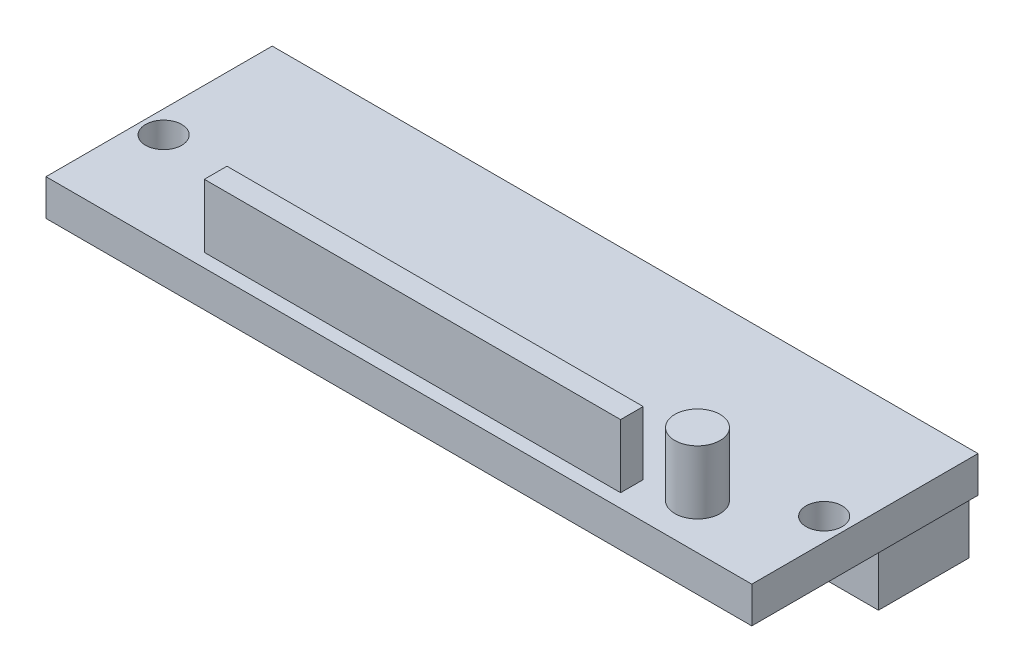
SolidWorks part; units mm, degrees
ref_plane "Front Plane" through (0, 0, 0) normal (0, 0, 1) x (1, 0, 0)
ref_plane "Top Plane" through (0, 0, 0) normal (0, 1, 0) x (1, 0, 0)
ref_plane "Right Plane" through (0, 0, 0) normal (1, 0, 0) x (0, 0, -1)
sketch "Sketch1" plane through (0, 0, 0) normal (0, 1, 0) x (1, 0, 0)
  line L1 (-39, -12.5) -> (39, -12.5)
  line L2 (-39, -12.5) -> (-39, 12.5)
  line L3 (-39, 12.5) -> (39, 12.5)
  line L4 (39, -12.5) -> (39, 12.5)
  line L5 (-39, -12.5) -> (39, 12.5) construction
  line L6 (-39, 12.5) -> (39, -12.5) construction
  point P0 (0, 0)
  dimension "D1" = 78
  dimension "D2" = 25
extrude "Boss-Extrude1" add sketch "Sketch1" along normal blind 4
sketch "Sketch2" plane through (0, 4, 0) normal (0, 1, 0) x (1, 0, 0)
  line L0 (-39, -12.5) -> (39, -12.5) construction
  line L1 (-23, -11) -> (23, -11)
  line L2 (-23, -11) -> (-23, -8.5)
  line L3 (-23, -8.5) -> (23, -8.5)
  line L4 (23, -11) -> (23, -8.5)
  line L5 (-23, -11) -> (23, -8.5) construction
  line L6 (-23, -8.5) -> (23, -11) construction
  line L7 (39, -12.5) -> (39, 12.5) construction
  circle A0 centre (28, -7.5) radius 2.5
  point P0 (0, -9.75)
  dimension "D6" = 5
  dimension "D1" = 46
  dimension "D2" = 2.5
  dimension "D3" = 1.5
  dimension "D4" = 11
  dimension "D5" = 5
extrude "Boss-Extrude2" add sketch "Sketch2" along normal blind 7
sketch "Sketch3" plane through (0, 0, 0) normal (0, -1, 0) x (1, 0, 0)
  line L0 (-39, -12.5) -> (-39, 12.5) construction
  line L1 (-38, -2.5) -> (-32.5, -2.5)
  line L2 (-38, -2.5) -> (-38, -12.5)
  line L3 (-38, -12.5) -> (-32.5, -12.5)
  line L4 (-32.5, -2.5) -> (-32.5, -12.5)
  line L6 (-27.9286, -2.5) -> (-22.4286, -2.5)
  line L7 (-27.9286, -2.5) -> (-27.9286, -12.5)
  line L8 (-27.9286, -12.5) -> (-22.4286, -12.5)
  line L9 (-22.4286, -2.5) -> (-22.4286, -12.5)
  line L10 (-17.8571, -2.5) -> (-12.3571, -2.5)
  line L11 (-17.8571, -2.5) -> (-17.8571, -12.5)
  line L12 (-17.8571, -12.5) -> (-12.3571, -12.5)
  line L13 (-12.3571, -2.5) -> (-12.3571, -12.5)
  line L14 (-7.7857, -2.5) -> (-2.2857, -2.5)
  line L15 (-7.7857, -2.5) -> (-7.7857, -12.5)
  line L16 (-7.7857, -12.5) -> (-2.2857, -12.5)
  line L17 (-2.2857, -2.5) -> (-2.2857, -12.5)
  line L18 (2.2857, -2.5) -> (7.7857, -2.5)
  line L19 (2.2857, -2.5) -> (2.2857, -12.5)
  line L20 (2.2857, -12.5) -> (7.7857, -12.5)
  line L21 (7.7857, -2.5) -> (7.7857, -12.5)
  line L22 (12.3571, -2.5) -> (17.8571, -2.5)
  line L23 (12.3571, -2.5) -> (12.3571, -12.5)
  line L24 (12.3571, -12.5) -> (17.8571, -12.5)
  line L25 (17.8571, -2.5) -> (17.8571, -12.5)
  line L26 (22.4286, -2.5) -> (27.9286, -2.5)
  line L27 (22.4286, -2.5) -> (22.4286, -12.5)
  line L28 (22.4286, -12.5) -> (27.9286, -12.5)
  line L29 (27.9286, -2.5) -> (27.9286, -12.5)
  line L30 (32.5, -2.5) -> (38, -2.5)
  line L31 (32.5, -2.5) -> (32.5, -12.5)
  line L32 (32.5, -12.5) -> (38, -12.5)
  line L33 (38, -2.5) -> (38, -12.5)
  line L34 (39, 12.5) -> (39, -12.5) construction
  line L35 (39, -12.5) -> (-39, -12.5) construction
  dimension "D1" = 5.5
  dimension "D2" = 1
  dimension "D3" = 10
  dimension "D5" = 1
  dimension "D4" = 8
extrude "Boss-Extrude3" add sketch "Sketch3" along normal blind 6.5
sketch "Sketch4" plane through (0, 4, 0) normal (0, 1, 0) x (1, 0, 0)
  line L1 (-39, 12.5) -> (-39, -12.5) construction
  line L2 (-39, -12.5) -> (39, -12.5) construction
  line L3 (0, 0) -> (0, -5.1553) construction
  circle A0 centre (-36.5, -2) radius 2
  circle A1 centre (36.5, -2) radius 2
  dimension "D2" = 4
  dimension "D1" = 2.5
  dimension "D3" = 10.5
extrude "Cut-Extrude1" cut sketch "Sketch4" against normal blind 10
